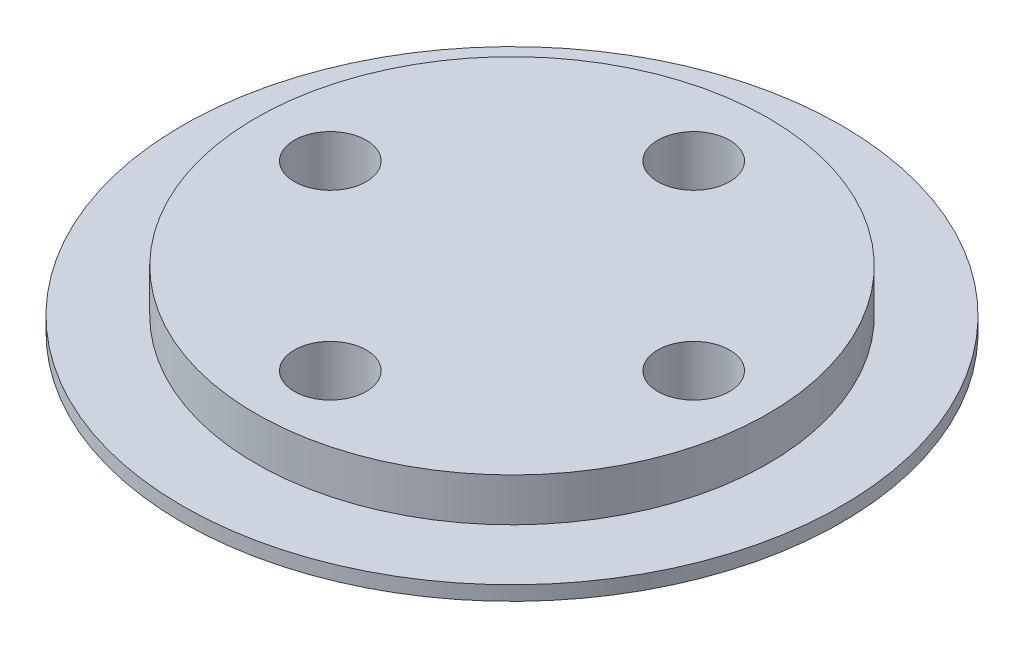
SolidWorks part; units mm, degrees
ref_plane "前基準面" through (0, 0, 0) normal (0, 0, 1) x (1, 0, 0)
ref_plane "上基準面" through (0, 0, 0) normal (0, 1, 0) x (1, 0, 0)
ref_plane "右基準面" through (0, 0, 0) normal (1, 0, 0) x (0, 0, -1)
sketch "草圖2" plane through (0, 0, 0) normal (0, 0, 1) x (1, 0, 0)
  line L0 (0, 0) -> (0, 20)
  line L1 (0, 20) -> (89, 20)
  line L2 (89, 20) -> (89, 5)
  line L3 (89, 5) -> (114.5, 5)
  line L4 (114.5, 5) -> (114.5, 0)
  line L5 (114.5, 0) -> (0, 0)
  dimension "D1" = 5
  dimension "D2" = 20
  dimension "D3" = 114.5
  dimension "D4" = 25.5
revolve "旋轉1" add sketch "草圖2" angle 360 about L0
sketch "草圖3" plane through (0, 20, 0) normal (0, 1, 0) x (1, 0, 0)
  line L0 (-138.5424, 0) -> (146.8483, 0) construction
  line L1 (0, 122.5951) -> (0, -122.9273) construction
  circle A0 centre (0, 63.1249) radius 12.5
  circle A1 centre (63.1249, 0) radius 12.5
  circle A2 centre (0, -63.1249) radius 12.5
  circle A3 centre (-63.1249, 0) radius 12.5
  point P16 (0, 0)
  dimension "D1" = 25
  dimension "D2" = 4
extrude "除料-伸長1" cut sketch "草圖3" against normal through all
